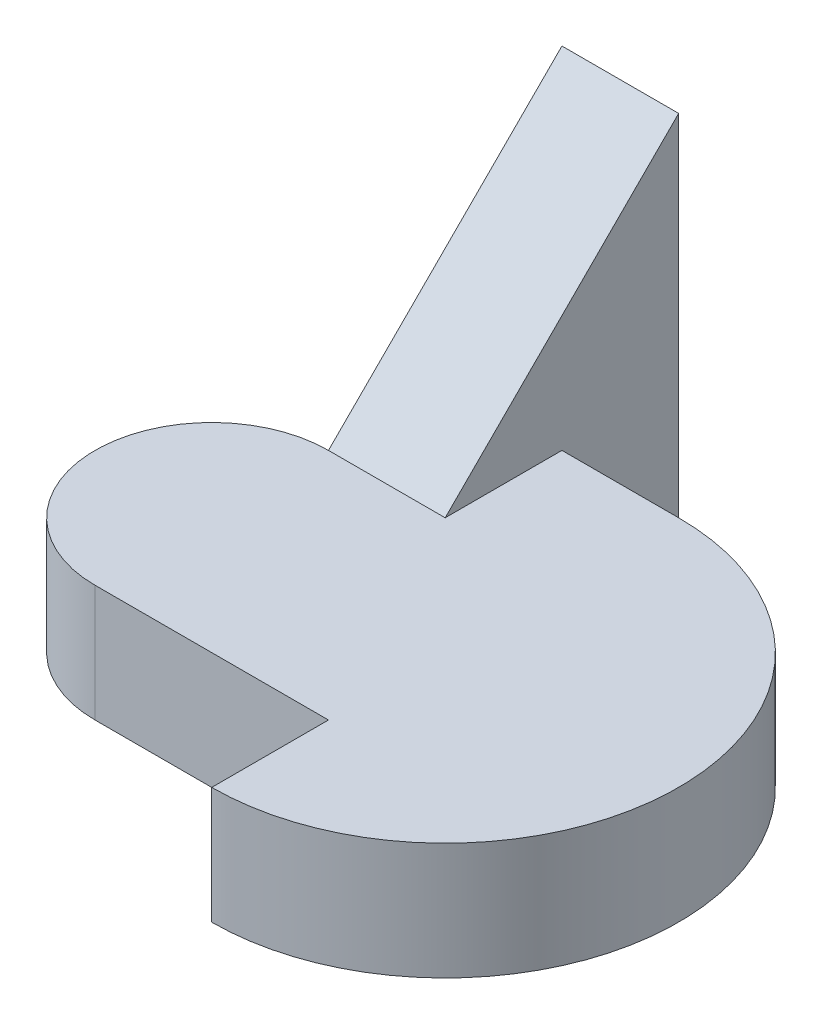
SolidWorks part; units mm, degrees
ref_plane "Front Plane" through (0, 0, 0) normal (0, 0, 1) x (1, 0, 0)
ref_plane "Top Plane" through (0, 0, 0) normal (0, 1, 0) x (1, 0, 0)
ref_plane "Right Plane" through (0, 0, 0) normal (1, 0, 0) x (0, 0, -1)
sketch "Sketch1" plane through (0, 0, 0) normal (0, 1, 0) x (1, 0, 0)
  line L0 (0, 20) -> (-10, 20)
  line L1 (-20, -10) -> (0, -10)
  line L2 (0, 0) -> (-20, 0) construction
  line L3 (0, -10) -> (0, -20)
  line L4 (-10, 20) -> (-10, 10)
  line L5 (-10, 10) -> (-20, 10)
  arc A0 (0, -20) -> (0, 20) centre (0, 0) ccw
  arc A1 (-20, 10) -> (-20, -10) centre (-20, 0) ccw
  dimension "D1" = 40
  dimension "D3" = 20
  dimension "D2" = 20
  dimension "D4" = 10
  dimension "D5" = 10
extrude "Boss-Extrude1" add sketch "Sketch1" along normal blind 10 contours A1 L1 L3 A0 L0 L4 L5
sketch "Sketch2" plane through (-10, 0, 0) normal (-1, 0, 0) x (0, 0, 1)
  line L0 (-10, 10) -> (-30, 30)
  line L1 (-30, 30) -> (-30, 0)
  line L2 (-30, 0) -> (-10, 0)
  line L3 (-10, 0) -> (-10, 10)
  dimension "D1" = 30
  dimension "D2" = 20
extrude "Boss-Extrude2" add sketch "Sketch2" along normal blind 10 contours L1 L2 L3 L0
